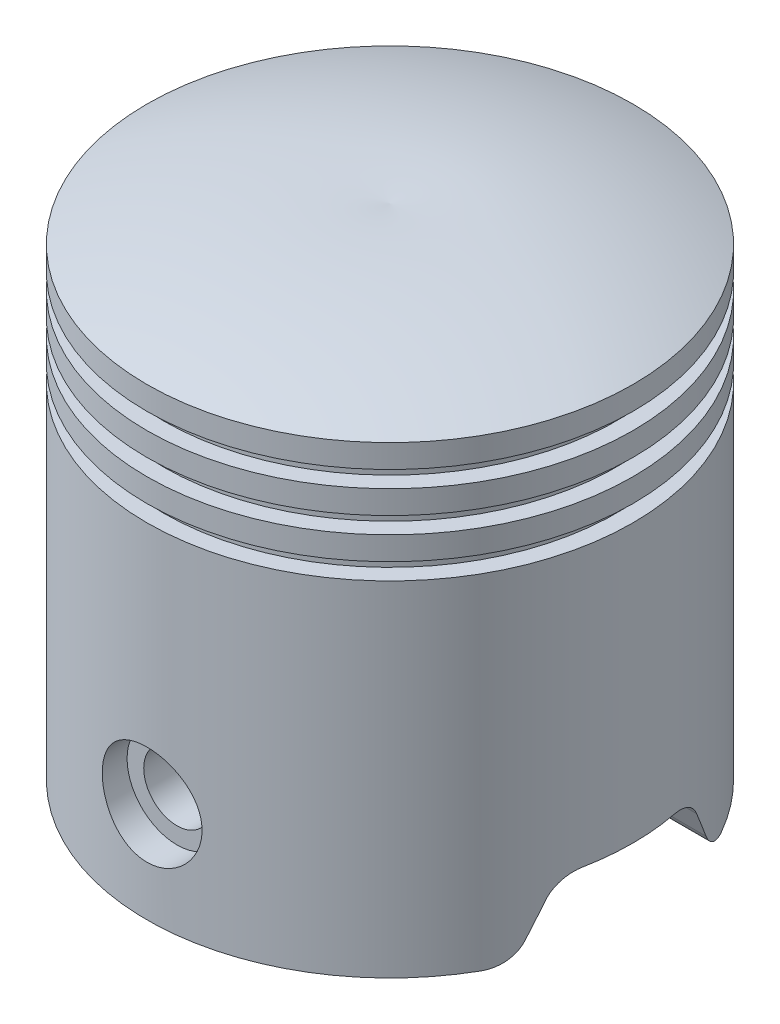
SolidWorks part; units mm, degrees
ref_plane "Front Plane" through (0, 0, 0) normal (0, 0, 1) x (1, 0, 0)
ref_plane "Top Plane" through (0, 0, 0) normal (0, 1, 0) x (1, 0, 0)
ref_plane "Right Plane" through (0, 0, 0) normal (1, 0, 0) x (0, 0, -1)
sketch "Sketch1" plane through (0, 0, 0) normal (0, 0, 1) x (1, 0, 0)
  line L0 (0, 65.6) -> (0, 70)
  line L2 (-36.5085, 69.6713) -> (-36.5085, 66.1713)
  line L3 (-36.5085, 66.1713) -> (-34.0085, 66.1713)
  line L4 (-34.0085, 66.1713) -> (-34.0085, 63.6713)
  line L5 (-34.0085, 63.6713) -> (-36.5085, 63.6713)
  line L6 (-36.5085, 63.6713) -> (-36.5085, 60.1713)
  line L7 (-36.5085, 60.1713) -> (-34.0085, 60.1713)
  line L8 (-34.0085, 60.1713) -> (-34.0085, 57.6713)
  line L9 (-34.0085, 57.6713) -> (-36.5085, 57.6713)
  line L10 (-36.5085, 57.6713) -> (-36.5085, 54.1713)
  line L11 (-36.5085, 54.1713) -> (-34.0085, 54.1713)
  line L12 (-34.0085, 54.1713) -> (-34.0085, 51.6713)
  line L13 (-34.0085, 51.6713) -> (-36.5085, 51.6713)
  line L14 (-36.5085, 51.6713) -> (-36.5085, 0)
  line L15 (-36.5085, 0) -> (-30.5085, 0)
  line L16 (-30.5085, 0) -> (-30.5085, 65.6)
  line L17 (-30.5085, 65.6) -> (0, 65.6)
  line L18 (0, 70) -> (0, 75)
  arc A0 (0, 75) -> (-36.5085, 69.6713) centre (-7.0114, -4.6922) ccw
  point P22 (-137.4076, 84.0048)
  dimension "D16" = 80
  dimension "D2" = 36.51
  dimension "D3" = 3.5
  dimension "D4" = 2.5
  dimension "D5" = 3.5
  dimension "D6" = 2.5
  dimension "D7" = 3.5
  dimension "D8" = 2.5
  dimension "D9" = 2.5
  dimension "D10" = 2.5
  dimension "D11" = 2.5
  dimension "D12" = 2.5
  dimension "D13" = 2.5
  dimension "D14" = 6
  dimension "D15" = 5
  dimension "D17" = 36.5085
  dimension "D18" = 65.6
revolve "Revolve1" add sketch "Sketch1" angle 360 about L18
sketch "Sketch2" plane through (0, 0, 0) normal (1, 0, 0) x (0, 0, -1)
  line L0 (-15, 0) -> (-10, 10)
  line L1 (-36.5085, 0) -> (36.5085, 0) construction
  line L2 (-10, 10) -> (10, 10)
  line L3 (10, 10) -> (15, 0)
  line L4 (-15, 0) -> (15, 0)
  point P4 (0, 10)
  dimension "D1" = 20
  dimension "D2" = 30
  dimension "D3" = 10
  dimension "D4" = 15
extrude "Cut-Extrude1" cut sketch "Sketch2" against normal up to next and the other way up to next
fillet "Fillet1" radius 5 8 edges at (31.9677, 10, -10) (-31.9677, 10, -10) (29.9255, 0, -15) (-29.9255, 0, -15) (31.9677, 10, 10) (-31.9677, 10, 10) (-29.9255, 0, 15) (29.9255, 0, 15)
sketch "Sketch3" plane through (0, 0, 0) normal (0, 0, 1) x (1, 0, 0)
  circle A0 centre (0, 15) radius 9
  dimension "D1" = 18
  dimension "D2" = 15
extrude "Boss-Extrude1" add sketch "Sketch3" along normal up to next and the other way up to next
sketch "Sketch4" plane through (0, 0, 0) normal (0, 0, 1) x (1, 0, 0)
  circle A0 centre (0, 15) radius 5
  dimension "D1" = 15
extrude "Cut-Extrude2" cut sketch "Sketch4" against normal up to next and the other way up to next
ref_plane "Plane1" through (0, 0, 32) normal (0, 0, 1) x (1, 0, 0)
sketch "Sketch5" plane through (0, 0, 32) normal (0, 0, 1) x (1, 0, 0)
  circle A0 centre (0, 15) radius 7.5
  dimension "D1" = 15
extrude "Cut-Extrude3" cut sketch "Sketch5" along normal blind 10
mirror "Mirror1" about plane through (0, 0, 0) normal (0, 0, 1) of "Cut-Extrude3"
